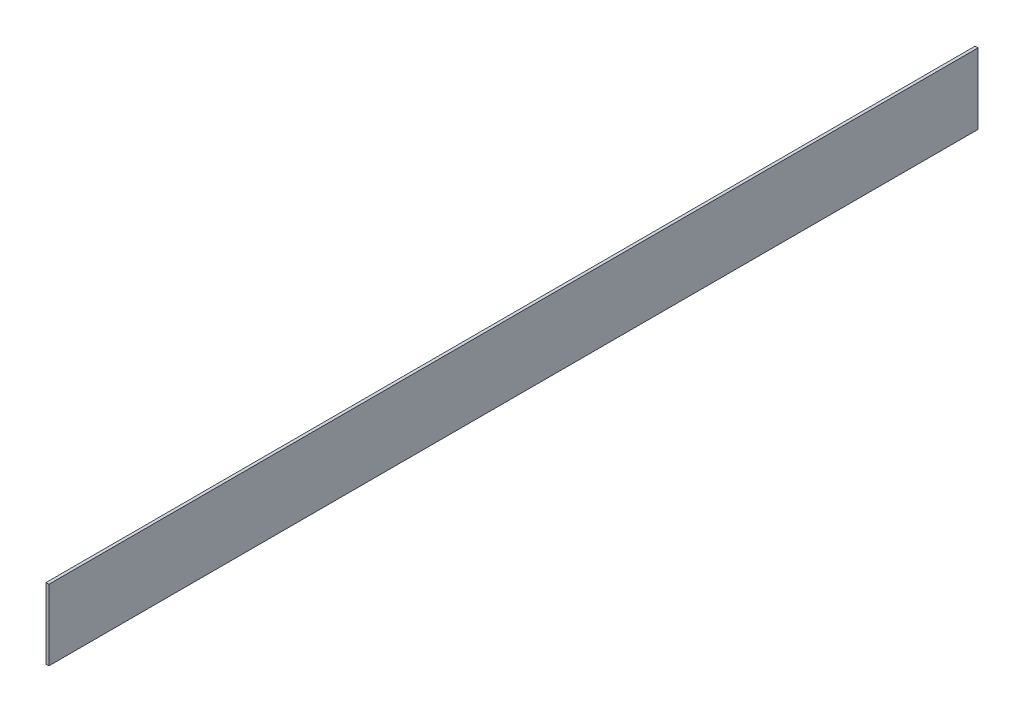
SolidWorks part; units mm, degrees
ref_plane "Front Plane" through (0, 0, 0) normal (0, 0, 1) x (1, 0, 0)
ref_plane "Top Plane" through (0, 0, 0) normal (0, 1, 0) x (1, 0, 0)
ref_plane "Right Plane" through (0, 0, 0) normal (1, 0, 0) x (0, 0, -1)
sketch "Sketch1" plane through (0, 0, 0) normal (1, 0, 0) x (0, 0, -1)
  line L1 (0, 0) -> (1000, 0)
  line L2 (0, 0) -> (0, -76.073)
  line L3 (0, -76.073) -> (1000, -76.073)
  line L4 (1000, 0) -> (1000, -76.073)
  dimension "D1" = 76.073
  dimension "D2" = 1000
extrude "Boss-Extrude1" add sketch "Sketch1" along normal blind 3.175
sketch "Sketch2" plane through (0, 0, 0) normal (0, 0, 1) x (1, 0, 0)
  line L0 (1.5875, 0) -> (1.5875, -76.073) construction
  line L1 (3.175, 0) -> (0, 0) construction
  line L2 (3.175, -76.073) -> (0, -76.073) construction
sketch "Sketch3" plane through (0, 0, -1000) normal (0, 0, -1) x (-1, 0, 0)
  line L0 (-1.5875, 0) -> (-1.5875, -76.073) construction
  line L1 (-3.175, 0) -> (0, 0) construction
  line L2 (-3.175, -76.073) -> (0, -76.073) construction
